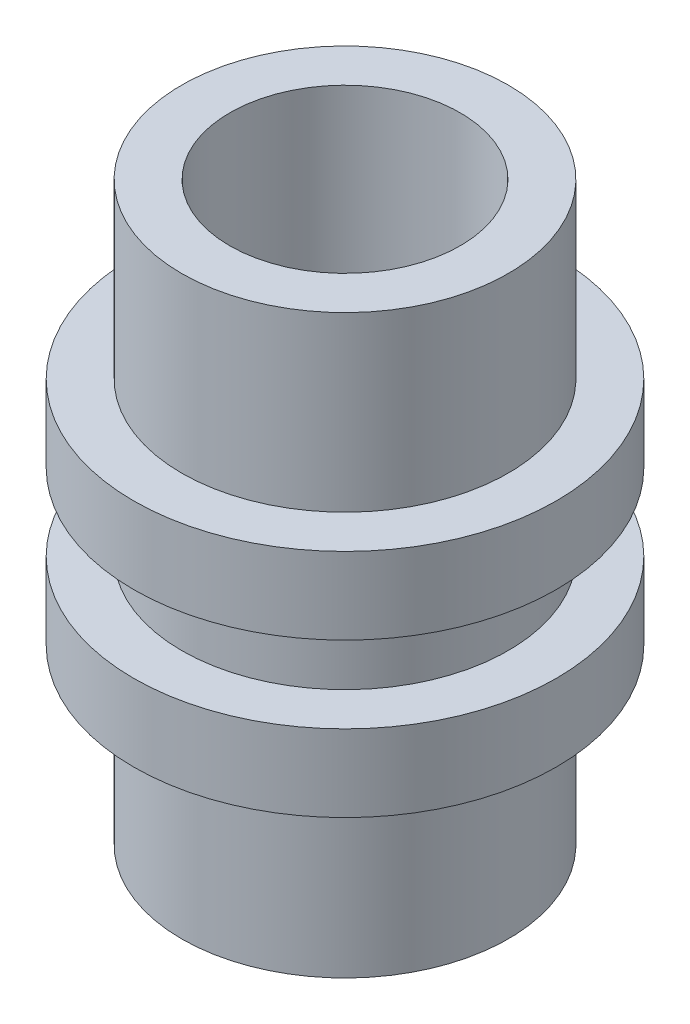
SolidWorks part; units mm, degrees
material "铸造合金钢"
ref_plane "前视基准面" through (0, 0, 0) normal (0, 0, 1) x (1, 0, 0)
ref_plane "上视基准面" through (0, 0, 0) normal (0, 1, 0) x (1, 0, 0)
ref_plane "右视基准面" through (0, 0, 0) normal (1, 0, 0) x (0, 0, -1)
sketch "草图1" plane through (0, 0, 0) normal (0, 1, 0) x (1, 0, 0)
  line L0 (0, 14.3323) -> (0, -15.2472) construction
  line L1 (-15.1496, 0) -> (19.0046, 0) construction
  circle A0 centre (0, 0) radius 5.5
  dimension "D1" = 11
extrude "拉伸1" add sketch "草图1" along normal blind 6
sketch "草图2" plane through (0, 6, 0) normal (0, 1, 0) x (-1, 0, 0)
  circle A0 centre (0, 0) radius 4.25
  circle A1 centre (0, 0) radius 3
  dimension "D1" = 8.5
  dimension "D2" = 6
extrude "拉伸2" add sketch "草图2" along normal blind 4.5 and the other way offset from surface (10.5 mm away) 4.5 other way up to face at (0, 0, 5.5)
ref_plane "基准面1" through (0, 4, 0) normal (0, 1, 0) x (-1, 0, 0)
sketch "草图3" plane through (0, 4, 0) normal (0, 1, 0) x (-1, 0, 0)
  circle A0 centre (0, 0) radius 5.5 construction
  circle A1 centre (0, 0) radius 4.25 construction
  circle A2 centre (0, 0) radius 5.5
  circle A3 centre (0, 0) radius 4.25
extrude "切除-拉伸1" cut sketch "草图3" against normal blind 2
